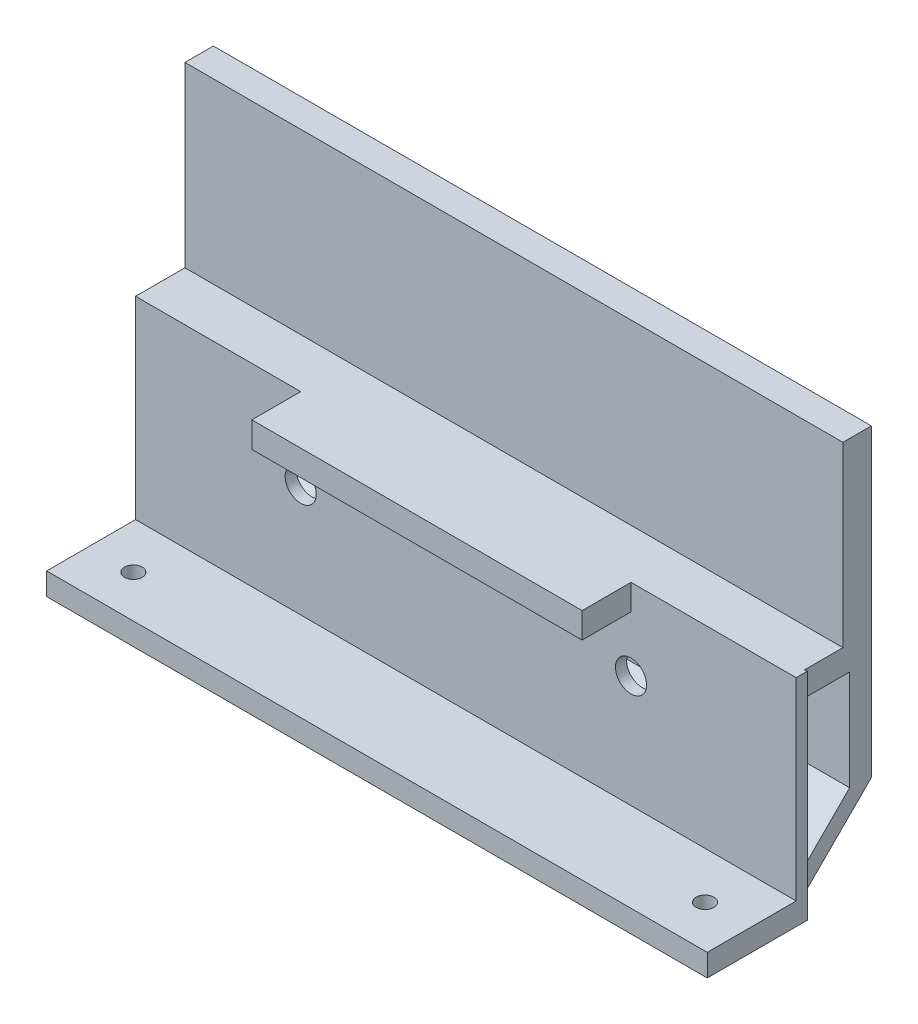
SolidWorks part; units mm, degrees
ref_plane "Plan de face" through (0, 0, 0) normal (0, 0, 1) x (1, 0, 0)
ref_plane "Plan de dessus" through (0, 0, 0) normal (0, 1, 0) x (1, 0, 0)
ref_plane "Plan de droite" through (0, 0, 0) normal (1, 0, 0) x (0, 0, -1)
sketch "Esquisse1" plane through (0, 0, 0) normal (0, 1, 0) x (1, 0, 0)
  line L0 (-79.4561, 18.9956) -> (69.1339, 18.9956)
  line L1 (-79.4561, 18.9956) -> (-79.4561, 38.9956)
  line L2 (-79.4561, 38.9956) -> (69.1339, 38.9956)
  line L3 (69.1339, 38.9956) -> (69.1339, 18.9956)
  line L4 (-79.4561, 18.9956) -> (-79.4561, 16.4956)
  line L5 (-79.4561, 16.4956) -> (69.1339, 16.4956)
  line L6 (69.1339, 16.4956) -> (69.1339, 18.9956)
extrude "Boss.-Extru.2" add sketch "Esquisse1" along normal blind 5 contours L5 L6 L0 L4 | L3 L2 L1 L0
sketch "Esquisse2" plane through (0, 0, -38.9956) normal (0, 0, -1) x (-1, 0, 0)
  line L0 (-69.1339, 48.5) -> (-69.1339, 5)
  line L1 (-69.1339, 48.5) -> (79.4561, 48.5)
  line L2 (-69.1339, 48.5) -> (79.4561, 48.5)
  line L3 (79.4561, 5) -> (-69.1339, 5)
  line L4 (-69.1339, 5) -> (79.4561, 5)
  line L5 (79.4561, 48.5) -> (79.4561, 5)
  line M8 (79.4561, 5) -> (-69.1339, 5)
extrude "Boss.-Extru.4" add sketch "Esquisse2" along normal blind 0.001 and the other way blind 2.5 contours L5 L1 L0 M8
sketch "Esquisse3" plane through (0, 0, 0) normal (0, -1, 0) x (1, 0, 0)
  line L0 (69.1339, -38.9956) -> (69.1339, -25.9956)
  line L1 (-79.4561, -38.9956) -> (-79.4561, -25.9956)
  line L2 (69.1339, -16.4956) -> (69.1339, -38.9956) construction
  line L3 (-79.4561, -38.9956) -> (-79.4561, -16.4956) construction
  line L5 (-79.4561, -25.9956) -> (-69.4561, -25.9956)
  line L6 (69.1339, -25.9956) -> (59.1339, -25.9956)
  circle A2 centre (-69.4561, -25.9956) radius 2
  circle A3 centre (59.1339, -25.9956) radius 2
  dimension "D1" = 13
  dimension "D2" = 13
extrude "Enlèv. mat.-Extru.1" cut sketch "Esquisse3" against normal blind 5
sketch "Esquisse4" plane through (-79.4561, 0, 0) normal (-1, 0, 0) x (0, 0, 1)
  line L0 (-38.9966, 48.5) -> (-53.9966, 48.5)
  line L6 (-53.9966, 15.001) -> (-53.9966, 48.5)
  line L7 (-38.9966, 5) -> (-53.9966, 20)
  line L8 (-38.9966, 5) -> (-38.9966, 48.5)
  line M10 (-38.9966, 48.5) -> (-38.9966, 5)
extrude "Boss.-Extru.9" add sketch "Esquisse4" against normal blind 148 contours L7 L0 L6 M10
sketch "Esquisse5" plane through (0, 0, -36.4956) normal (0, 0, 1) x (1, 0, 0)
  line L0 (69.1339, 26.75) -> (69.1339, 33.75)
  line L1 (69.1339, 48.5) -> (69.1339, 5) construction
  line L2 (69.1339, 26.75) -> (-79.4561, 26.75)
  line L3 (-79.4561, 48.5) -> (-79.4561, 5) construction
  line L4 (-79.4561, 26.75) -> (-79.4561, 33.75)
  line L5 (-79.4561, 33.75) -> (69.1339, 33.75)
  line L6 (-5.1611, 26.75) -> (69.1339, 26.75)
  line L7 (-5.1611, 26.75) -> (-79.4561, 26.75)
  line L8 (31.9864, 26.75) -> (31.9864, 33.75)
  line L9 (-42.3086, 26.75) -> (-42.3086, 33.75)
  circle A0 centre (31.9864, 30.25) radius 3.5
  circle A1 centre (-42.3086, 30.25) radius 3.5
extrude "Enlèv. mat.-Extru.2" cut sketch "Esquisse5" against normal blind 148 contours L8 A0 | L8 A0 | L9 A1 | L9 A1
sketch "Esquisse6" plane through (68.5439, 0, 0) normal (1, 0, 0) x (0, 0, -1)
  line L0 (38.9966, 43.0152) -> (49.1099, 43.0152)
  line L1 (38.9966, 48.5) -> (38.9966, 5) construction
  line L2 (49.1099, 43.0152) -> (49.1099, 20.4503)
  line L3 (49.1099, 20.4503) -> (38.9966, 10.3369)
  line L4 (38.9966, 10.3369) -> (38.9966, 43.0152)
extrude "Enlèv. mat.-Extru.3" cut sketch "Esquisse6" against normal blind 158
sketch "Esquisse7" plane through (0, 0, -36.4956) normal (0, 0, 1) x (1, 0, 0)
  line L0 (31.9864, 33.75) -> (31.9864, 42.75)
  line L1 (-42.3086, 33.75) -> (-42.3086, 42.75)
  line L2 (31.9864, 42.75) -> (-42.3086, 42.75)
  line L3 (-42.3086, 42.75) -> (-42.3086, 48.5)
  line L4 (69.1339, 48.5) -> (-79.4561, 48.5) construction
  line L5 (-42.3086, 48.5) -> (31.9864, 48.5)
  line L6 (31.9864, 48.5) -> (31.9864, 42.75)
  circle A0 centre (31.9864, 30.25) radius 3.5 construction
  circle A1 centre (-42.3086, 30.25) radius 3.5 construction
  line M6 (69.1339, 48.5) -> (-79.4561, 48.5)
extrude "Boss.-Extru.10" add sketch "Esquisse7" along normal blind 11 contours L6 L3 L2 M6
sketch "Esquisse8" plane through (0, 48.5, 0) normal (0, 1, 0) x (1, 0, 0)
  line L0 (-79.4561, 53.9966) -> (-79.4561, 47.5966)
  line L1 (-79.4561, 36.4956) -> (-79.4561, 53.9966) construction
  line L2 (68.5439, 53.9966) -> (-79.4561, 53.9966) construction
  line L3 (68.5439, 53.9966) -> (68.5439, 47.5966)
  line L4 (68.5439, 38.9966) -> (68.5439, 53.9966) construction
  line L5 (68.5439, 47.5966) -> (-79.4561, 47.5966)
  line L6 (-79.4561, 53.9966) -> (68.5439, 53.9966)
extrude "Boss.-Extru.11" add sketch "Esquisse8" along normal blind 40
